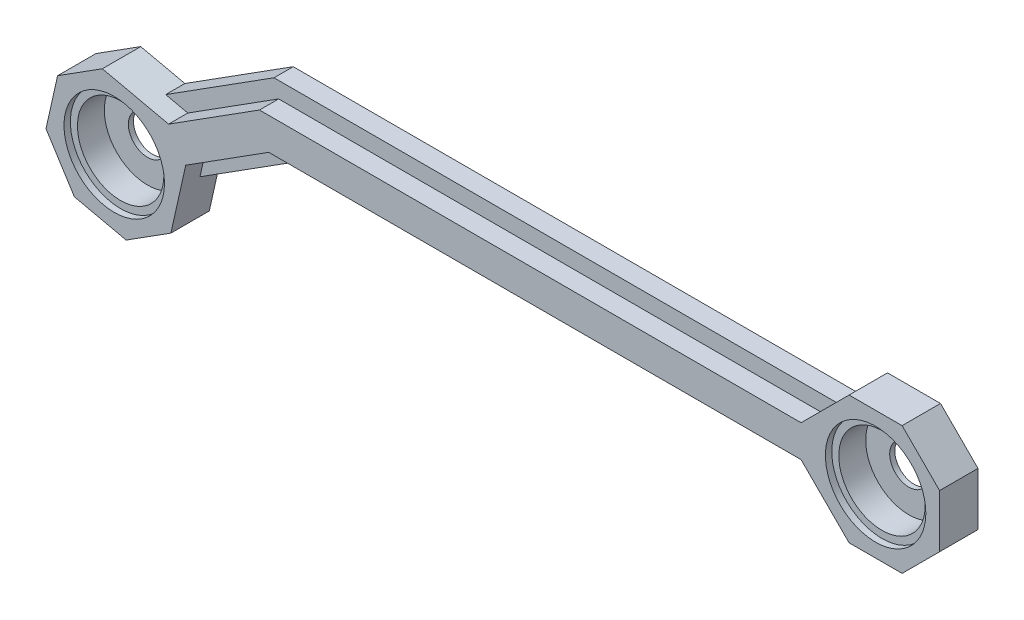
SolidWorks part; units mm, degrees
material "AISI 1020"
ref_plane "Front Plane" through (0, 0, 0) normal (0, 0, 1) x (1, 0, 0)
ref_plane "Top Plane" through (0, 0, 0) normal (0, 1, 0) x (1, 0, 0)
ref_plane "Right Plane" through (0, 0, 0) normal (1, 0, 0) x (0, 0, -1)
sketch "Sketch1" plane through (0, 0, 0) normal (0, 0, 1) x (1, 0, 0)
  line L0 (0, 0) -> (-95.55, 0) construction
  line L1 (-95.55, 0) -> (-118.9664, -14.8548) construction
  line L2 (-108.5682, -14.1796) -> (-94.0978, -5)
  line L3 (4.1421, 10) -> (-4.1421, 10)
  line L4 (-4.1421, 10) -> (-10, 4.1421)
  line L6 (-10, -4.1421) -> (-4.1421, -10)
  line L7 (-4.1421, -10) -> (4.1421, -10)
  line L8 (4.1421, -10) -> (10, -4.1421)
  line L9 (10, -4.1421) -> (10, 4.1421)
  line L10 (10, 4.1421) -> (4.1421, 10)
  line L11 (-127.8209, -8.6294) -> (-129.6295, -16.7139)
  line L12 (-129.6295, -16.7139) -> (-125.1918, -23.7093)
  line L13 (-125.1918, -23.7093) -> (-117.1073, -25.5178)
  line L14 (-117.1073, -25.5178) -> (-110.1119, -21.0801)
  line L15 (-110.1119, -21.0801) -> (-108.3033, -12.9957)
  line L17 (-112.7411, -6.0003) -> (-120.8255, -4.1917)
  line L18 (-120.8255, -4.1917) -> (-127.8209, -8.6294)
  line L19 (-94.0978, -5) -> (-9.1421, -5)
  line L20 (-97.0022, 5) -> (-9.1421, 5)
  line L21 (-113.925, -5.7354) -> (-97.0022, 5)
  line L22 (-94.0978, -5) -> (-97.0022, 5)
  line L23 (-120.8255, -4.1917) -> (-110.4747, -6.5073)
  line L24 (-4.1421, 10) -> (-11.6421, 2.5)
  line L25 (-4.1421, -10) -> (-11.6421, -2.5)
  line L26 (-110.1119, -21.0801) -> (-107.7963, -10.7294)
  line L27 (-11.6421, 2.5) -> (-96.2761, 2.5)
  line L28 (-96.2761, 2.5) -> (-110.4747, -6.5073)
  line L29 (-94.8239, -2.5) -> (-107.7963, -10.7294)
  line L30 (-11.6421, -2.5) -> (-94.8239, -2.5)
  line L31 (-94.8239, -2.5) -> (-107.7963, -10.7294)
  line L32 (-108.3033, -12.9957) -> (-110.5222, -9.498) [skipped]
  line L33 (-10, 0) -> (-10, -4.1421) [skipped]
  arc A0 (-7.0711, -7.0711) -> (-7.0711, 7.0711) centre (0, 0) ccw construction
  arc A1 (-116.7833, -5.096) -> (-109.2076, -17.0379) centre (-118.9664, -14.8548) ccw construction
  circle A2 centre (-118.9664, -14.8548) radius 3
  circle A3 centre (-0.8766, 0) radius 3
  dimension "D1" = 95.55
  dimension "D2" = 20
  dimension "D3" = 20
  dimension "D4" = 147.61
  dimension "D5" = 10
  dimension "D6" = 26.75
  dimension "D7" = 10
  dimension "D8" = 5
extrude "Boss-Extrude1" add sketch "Sketch1" against normal blind 6 contours L29 L22 L28 L23 L17 L18 L11 L12 L13 L14 L15 L26 A2 | L30 L25 L6 L7 L8 L9 L10 L3 L4 L24 L27 L22 A3
sketch "Sketch2" plane through (0, 0, 0) normal (0, 0, 1) x (1, 0, 0)
  line L0 (-113.925, -5.7354) -> (-110.4747, -6.5073)
  line L1 (-110.4747, -6.5073) -> (-96.2761, 2.5)
  line L2 (-96.2761, 2.5) -> (-11.6421, 2.5)
  line L3 (-11.6421, 2.5) -> (-9.1421, 5)
  line L4 (-9.1421, 5) -> (-97.0022, 5)
  line L5 (-97.0022, 5) -> (-113.925, -5.7354)
  line L6 (-108.5682, -14.1796) -> (-107.7963, -10.7294)
  line L7 (-107.7963, -10.7294) -> (-94.8239, -2.5)
  line L8 (-94.8239, -2.5) -> (-11.6421, -2.5)
  line L9 (-11.6421, -2.5) -> (-9.1421, -5)
  line L10 (-9.1421, -5) -> (-94.0978, -5)
  line L11 (-94.0978, -5) -> (-108.5682, -14.1796)
extrude "Boss-Extrude2" add sketch "Sketch2" against normal blind 3
sketch "Sketch3" plane through (0, 0, -6) normal (0, 0, -1) x (-1, 0, 0)
  circle A0 centre (0, 0) radius 7.85
  circle A1 centre (118.9664, -14.8548) radius 7.85
extrude "Cut-Extrude1" cut sketch "Sketch3" against normal blind 1
sketch "Sketch4" plane through (0, 0, -6) normal (0, 0, -1) x (-1, 0, 0)
  circle A0 centre (0, 0) radius 6.75
  circle A1 centre (118.9664, -14.8548) radius 6.75
extrude "Cut-Extrude2" cut sketch "Sketch4" against normal blind 5.2
sketch "Sketch5" plane through (0, 0, 0) normal (0, 0, 1) x (1, 0, 0)
  line L1 (-6.0261, -3.3388) -> (4.2729, -3.3388)
  line L2 (-6.0261, -3.3388) -> (-6.0261, 3.3388)
  line L3 (-6.0261, 3.3388) -> (4.2729, 3.3388)
  line L4 (4.2729, -3.3388) -> (4.2729, 3.3388)
  line L5 (-6.0261, -3.3388) -> (4.2729, 3.3388) construction
  line L6 (-6.0261, 3.3388) -> (4.2729, -3.3388) construction
  point P0 (-0.8766, 0)
extrude "Boss-Extrude3" add sketch "Sketch5" against normal blind 0.8
sketch "Sketch6" plane through (0, 0, 0) normal (0, 0, 1) x (1, 0, 0)
  circle A0 centre (0, 0) radius 3
extrude "Cut-Extrude3" cut sketch "Sketch6" against normal blind 0.8
sketch "Sketch7" plane through (0, 0, -6) normal (0, 0, -1) x (-1, 0, 0)
  circle A0 centre (0, 0) radius 3
  circle A1 centre (0, 0) radius 9.0718
  circle A2 centre (118.9664, -14.8548) radius 3
  circle A3 centre (118.9664, -14.8548) radius 8.5301
extrude "Boss-Extrude5" add sketch "Sketch7" against normal blind 6 contours A1 | A0 | A3 | A2
sketch "Sketch8" plane through (0, 0, 0) normal (0, 0, 1) x (1, 0, 0)
  circle A0 centre (-118.9664, -14.8548) radius 7.85
  circle A1 centre (0, 0) radius 7.85
extrude "Cut-Extrude4" cut sketch "Sketch8" against normal blind 1
sketch "Sketch9" plane through (0, 0, 0) normal (0, 0, 1) x (1, 0, 0)
  circle A0 centre (-118.9664, -14.8548) radius 6.75
  circle A1 centre (0, 0) radius 6.75
extrude "Cut-Extrude5" cut sketch "Sketch9" against normal blind 5.2
sketch "Sketch10" plane through (0, 0, -3) normal (0, 0, -1) x (-1, 0, 0)
  line L0 (9.1421, -5) -> (11.6421, -2.5)
  line L1 (11.6421, -2.5) -> (94.8239, -2.5)
  line L2 (94.8239, -2.5) -> (107.7963, -10.7294)
  line L3 (107.7963, -10.7294) -> (108.5682, -14.1796)
  line L4 (108.5682, -14.1796) -> (94.0978, -5)
  line L5 (94.0978, -5) -> (9.1421, -5) construction
  line L6 (108.5682, -14.1796) -> (94.0978, -5) construction
  line L7 (94.0978, -5) -> (9.1421, -5)
  line L8 (9.1421, 5) -> (11.6421, 2.5)
  line L9 (11.6421, 2.5) -> (96.2761, 2.5)
  line L10 (96.2761, 2.5) -> (110.4747, -6.5073)
  line L11 (110.4747, -6.5073) -> (113.925, -5.7354)
  line L12 (113.925, -5.7354) -> (97.0022, 5)
  line L13 (97.0022, 5) -> (9.1421, 5)
extrude "Boss-Extrude6" add sketch "Sketch10" along normal blind 3
sketch "Sketch11" plane through (0, 0, 0) normal (0, 0, 1) x (1, 0, 0)
  line L0 (-107.7963, -10.7294) -> (-108.5682, -14.1796)
  line L1 (-108.5682, -14.1796) -> (-94.0978, -5)
  line L2 (-94.0978, -5) -> (-9.1421, -5)
  line L3 (-9.1421, -5) -> (-11.6421, -2.5)
  line L4 (-11.6421, -2.5) -> (-94.8239, -2.5)
  line L5 (-94.8239, -2.5) -> (-107.7963, -10.7294)
  line L6 (-107.7963, -10.7294) -> (-108.5682, -14.1796)
  line L7 (-107.7963, -10.7294) -> (-94.8239, -2.5)
  line L8 (-94.8239, -2.5) -> (-11.6421, -2.5)
  line L9 (-11.6421, -2.5) -> (-9.1421, -5)
  line L10 (-9.1421, -5) -> (-94.0978, -5)
  line L11 (-108.5682, -14.1796) -> (-94.0978, -5)
  line L12 (-113.925, -5.7354) -> (-110.4747, -6.5073)
  line L13 (-110.4747, -6.5073) -> (-96.2761, 2.5)
  line L14 (-96.2761, 2.5) -> (-11.6421, 2.5)
  line L15 (-11.6421, 2.5) -> (-9.1421, 5)
  line L16 (-9.1421, 5) -> (-97.0022, 5)
  line L17 (-97.0022, 5) -> (-113.925, -5.7354)
extrude "Cut-Extrude10" cut sketch "Sketch11" against normal blind 3 contours L16 L17 L12 L13 L14 L15 | L4 L5 L0 L1 L2 L3
equation "\"A\"= 100"
equation "\"B\"= 100"
equation "\"C\"= 100"
equation "\"D\"= 100"
equation "\"E\"= 100"
